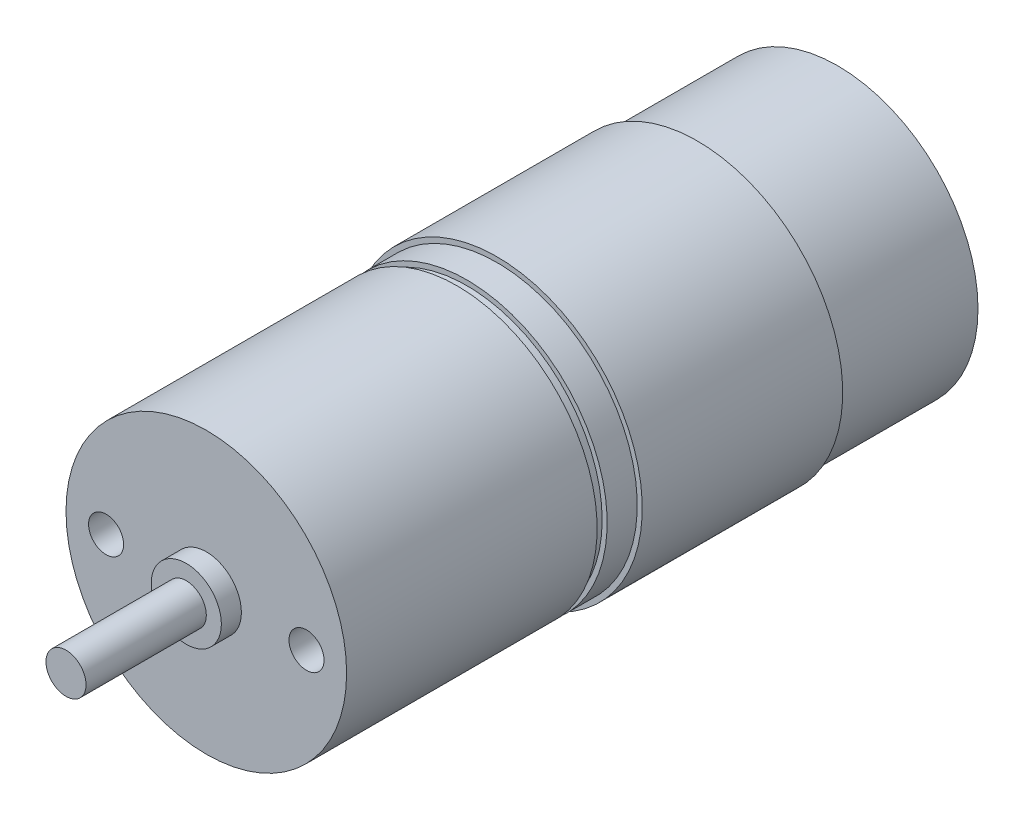
SolidWorks part; units mm, degrees
ref_plane "Front Plane" through (0, 0, 0) normal (0, 0, 1) x (1, 0, 0)
ref_plane "Top Plane" through (0, 0, 0) normal (0, 1, 0) x (1, 0, 0)
ref_plane "Right Plane" through (0, 0, 0) normal (1, 0, 0) x (0, 0, -1)
sketch "Sketch1" plane through (0, 0, 0) normal (0, 0, 1) x (1, 0, 0)
  circle A0 centre (0, 0) radius 14
  dimension "D1" = 28
extrude "Boss-Extrude1" add sketch "Sketch1" along normal blind 63
sketch "Sketch2" plane through (0, 0, 63) normal (0, 0, 1) x (1, 0, 0)
  circle A0 centre (0, 0) radius 3.5
  dimension "D1" = 7
extrude "Boss-Extrude2" add sketch "Sketch2" along normal blind 2
sketch "Sketch3" plane through (0, 0, 65) normal (0, 0, 1) x (1, 0, 0)
  circle A0 centre (0, 0) radius 2
  dimension "D1" = 4
extrude "Boss-Extrude3" add sketch "Sketch3" along normal blind 12
ref_plane "Plane1" through (0, 0, 14) normal (0, 0, -1) x (-1, 0, 0)
sketch "Sketch4" plane through (0, 0, 14) normal (0, 0, -1) x (-1, 0, 0)
  circle A0 centre (0, 0) radius 14.5
  dimension "D1" = 29
extrude "Boss-Extrude4" add sketch "Sketch4" against normal blind 20
ref_plane "Plane2" through (0, 0, 37) normal (0, 0, -1) x (-1, 0, 0)
sketch "Sketch5" plane through (0, 0, 37) normal (0, 0, -1) x (-1, 0, 0)
  circle A0 centre (0, 0) radius 13.5
  dimension "D1" = 27
extrude "Cut-Extrude1" cut sketch "Sketch5" against normal blind 1 flip side to cut
sketch "Sketch6" plane through (0, 0, 63) normal (0, 0, 1) x (1, 0, 0)
  line L0 (-10, 0) -> (10, 0) construction
  circle A0 centre (-10, 0) radius 1.75
  circle A1 centre (10, 0) radius 1.75
  dimension "D1" = 3.5
  dimension "D2" = 20
extrude "Cut-Extrude2" cut sketch "Sketch6" against normal blind 10
